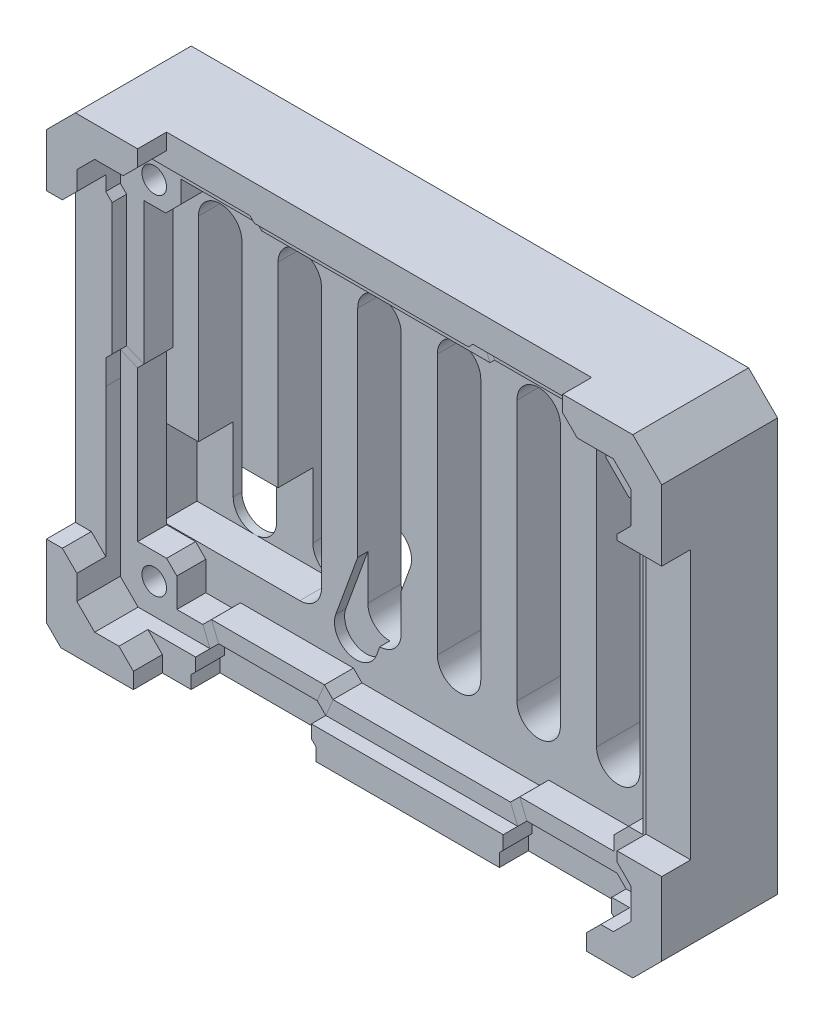
SolidWorks part; units mm, degrees
ref_plane "前视基准面" through (0, 0, 0) normal (0, 0, 1) x (1, 0, 0)
ref_plane "上视基准面" through (0, 0, 0) normal (0, 1, 0) x (1, 0, 0)
ref_plane "右视基准面" through (0, 0, 0) normal (1, 0, 0) x (0, 0, -1)
other "Configuration Table"
sketch "草图1" plane through (0, 0, 0) normal (0, 0, 1) x (1, 0, 0)
  line L1 (0, 0) -> (75, 0)
  line L2 (0, 0) -> (0, -55)
  line L3 (0, -55) -> (75, -55)
  line L4 (75, 0) -> (75, -55)
  dimension "D1" = 55
  dimension "D2" = 75
extrude "凸台-拉伸1" add sketch "草图1" along normal blind 12
sketch "草图2" plane through (0, 0, 0) normal (0, 0, -1) x (-1, 0, 0)
  circle A0 centre (-71.1669, -3.5575) radius 1.7
  circle A1 centre (-71.1669, -51.5849) radius 1.7
  circle A2 centre (-3.8888, -51.5849) radius 1.7
  circle A3 centre (-3.8888, -3.5575) radius 1.7
  dimension "D1" = 3.4
  dimension "D2" = 3.4
  dimension "D3" = 3.4
  dimension "D4" = 3.4
extrude "切除-拉伸1" cut sketch "草图2" against normal blind 12
sketch "草图3" plane through (0, 0, 0) normal (0, 0, -1) x (-1, 0, 0)
  line L1 (-73.9669, -0.7575) -> (-68.3669, -0.7575)
  line L2 (-73.9669, -0.7575) -> (-73.9669, -6.3575)
  line L3 (-73.9669, -6.3575) -> (-68.3669, -6.3575)
  line L4 (-68.3669, -0.7575) -> (-68.3669, -6.3575)
  line L5 (-73.9669, -0.7575) -> (-68.3669, -6.3575) construction
  line L6 (-73.9669, -6.3575) -> (-68.3669, -0.7575) construction
  line L11 (-6.6888, -0.7575) -> (-1.0888, -0.7575)
  line L12 (-6.6888, -0.7575) -> (-6.6888, -6.3575)
  line L13 (-6.6888, -6.3575) -> (-1.0888, -6.3575)
  line L14 (-1.0888, -0.7575) -> (-1.0888, -6.3575)
  line L15 (-6.6888, -0.7575) -> (-1.0888, -6.3575) construction
  line L16 (-6.6888, -6.3575) -> (-1.0888, -0.7575) construction
  line L17 (-73.9669, -48.7849) -> (-68.3669, -48.7849)
  line L18 (-73.9669, -48.7849) -> (-73.9669, -54.3849)
  line L19 (-73.9669, -54.3849) -> (-68.3669, -54.3849)
  line L20 (-68.3669, -48.7849) -> (-68.3669, -54.3849)
  line L21 (-73.9669, -48.7849) -> (-68.3669, -54.3849) construction
  line L22 (-73.9669, -54.3849) -> (-68.3669, -48.7849) construction
  line L23 (-6.6888, -48.7849) -> (-1.0888, -48.7849)
  line L24 (-6.6888, -48.7849) -> (-6.6888, -54.3849)
  line L25 (-6.6888, -54.3849) -> (-1.0888, -54.3849)
  line L26 (-1.0888, -48.7849) -> (-1.0888, -54.3849)
  line L27 (-6.6888, -48.7849) -> (-1.0888, -54.3849) construction
  line L28 (-6.6888, -54.3849) -> (-1.0888, -48.7849) construction
  circle A0 centre (-71.1669, -3.5575) radius 1.7 construction
  circle A1 centre (-3.8888, -3.5575) radius 1.7 construction
  circle A2 centre (-71.1669, -51.5849) radius 1.7 construction
  circle A3 centre (-3.8888, -51.5849) radius 1.7 construction
  point P0 (-71.1669, -3.5575)
  point P8 (-71.1669, -51.5849)
  point P12 (-3.8888, -3.5575)
  point P22 (-3.8888, -51.5849)
  dimension "D1" = 5.6
  dimension "D2" = 5.6
  dimension "D3" = 5.6
  dimension "D4" = 5.6
  dimension "D5" = 5.6
  dimension "D6" = 5.6
  dimension "D7" = 5.6
  dimension "D8" = 5.6
extrude "切除-拉伸2" cut sketch "草图3" along normal blind 2.5 from offset 4 offset against normal yes
sketch "草图5" plane through (0, 0, 0) normal (0, 0, -1) x (-1, 0, 0)
  line L1 (-80, 5) -> (5, 5)
  line L2 (-80, 5) -> (-80, -60)
  line L3 (-80, -60) -> (5, -60)
  line L4 (5, 5) -> (5, -60)
  line L5 (-80, 5) -> (5, -60) construction
  line L6 (-80, -60) -> (5, 5) construction
  line L10 (-75, 0) -> (0, 0) construction
  line L11 (0, 0) -> (0, -55) construction
  line L12 (-75, -55) -> (-75, 0) construction
  line L13 (-75, 0) -> (0, 0)
  line L14 (-75, 0) -> (-75, -55)
  line L15 (-75, -55) -> (0, -55)
  line L16 (0, 0) -> (0, -55)
  line L17 (0, -55) -> (-75, -55) construction
  point P0 (-37.5, -27.5)
  dimension "D1" = 65
  dimension "D2" = 85
  dimension "D3" = 5
  dimension "D4" = 5
extrude "凸台-拉伸2" add sketch "草图5" against normal up to surface (12 mm away) up to face at (2.1888, -3.5575, 12)
sketch "草图6" plane through (0, 0, 12) normal (0, 0, 1) x (1, 0, 0)
  line L56 (0.8713, -25.6658) -> (0, -26.5371)
  line L57 (0, -26.5371) -> (0, -53.0074)
  line L58 (0, -53.0074) -> (1.9926, -55)
  line L59 (1.9926, -55) -> (11.2697, -55)
  line L60 (11.2697, -55) -> (12.4616, -53.8134)
  line L61 (12.4616, -53.8134) -> (26.7436, -53.8171)
  line L62 (26.7436, -53.8171) -> (27.9265, -55)
  line L63 (27.9265, -55) -> (53.7727, -55)
  line L64 (53.7727, -55) -> (55.0435, -53.7345)
  line L65 (55.0435, -53.7345) -> (68.1524, -53.7382)
  line L66 (68.1524, -53.7382) -> (69.4142, -55)
  line L67 (69.4142, -55) -> (72.9822, -55)
  line L68 (72.9822, -55) -> (74.9747, -53.0074)
  line L69 (74.9747, -53.0074) -> (74.9747, -49.4917)
  line L70 (74.9747, -49.4917) -> (73.0283, -47.54)
  line L71 (73.0283, -47.54) -> (73.032, -7.6469)
  line L72 (73.032, -7.6469) -> (74.9747, -5.7042)
  line L73 (74.9747, -5.7042) -> (74.9747, -2.0179)
  line L74 (74.9747, -2.0179) -> (72.9822, -0.0253)
  line L75 (72.9822, -0.0253) -> (50.2451, -0.0253)
  line L76 (50.2451, -0.0253) -> (49.6148, -0.6503)
  line L77 (49.6148, -0.6503) -> (19.3949, -0.6466)
  line L78 (19.3949, -0.6466) -> (18.7736, -0.0253)
  line L79 (18.7736, -0.0253) -> (1.9926, -0.0253)
  line L80 (1.9926, -0.0253) -> (0, -2.0179)
  line L81 (0, -2.0179) -> (0, -5.9826)
  line L82 (0, -5.9826) -> (0.875, -6.8629)
  line L83 (0.875, -6.8629) -> (0.8713, -25.6658)
extrude "切除-拉伸3" cut sketch "草图6" against normal blind 2
sketch "草图7" plane through (0, 0, 10) normal (0, 0, 1) x (1, 0, 0)
  line L28 (0.875, -6.8629) -> (0.8713, -25.6658)
  line L29 (0.8713, -25.6658) -> (0, -26.5371)
  line L30 (0, -26.5371) -> (0, -53.0074)
  line L31 (0, -53.0074) -> (1.9926, -55)
  line L32 (1.9926, -55) -> (11.2697, -55)
  line L33 (11.2697, -55) -> (12.4616, -53.8134)
  line L34 (12.4616, -53.8134) -> (26.7436, -53.8171)
  line L35 (26.7436, -53.8171) -> (27.9265, -55)
  line L36 (27.9265, -55) -> (53.7727, -55)
  line L37 (53.7727, -55) -> (55.0435, -53.7345)
  line L38 (55.0435, -53.7345) -> (68.1524, -53.7382)
  line L39 (68.1524, -53.7382) -> (69.4142, -55)
  line L40 (69.4142, -55) -> (72.9822, -55)
  line L41 (72.9822, -55) -> (74.9747, -53.0074)
  line L42 (74.9747, -53.0074) -> (74.9747, -49.4917)
  line L43 (74.9747, -49.4917) -> (73.0283, -47.54)
  line L44 (73.0283, -47.54) -> (73.032, -7.6469)
  line L45 (73.032, -7.6469) -> (74.9747, -5.7042)
  line L46 (74.9747, -5.7042) -> (74.9747, -2.0179)
  line L47 (74.9747, -2.0179) -> (72.9822, -0.0253)
  line L48 (72.9822, -0.0253) -> (50.2451, -0.0253)
  line L49 (50.2451, -0.0253) -> (49.6148, -0.6503)
  line L50 (49.6148, -0.6503) -> (19.3949, -0.6466)
  line L51 (19.3949, -0.6466) -> (18.7736, -0.0253)
  line L52 (18.7736, -0.0253) -> (1.9926, -0.0253)
  line L53 (1.9926, -0.0253) -> (0, -2.0179)
  line L54 (0, -2.0179) -> (0, -5.9826)
  line L55 (0, -5.9826) -> (0.875, -6.8629)
  line L56 (0.875, -6.8629) -> (0.8713, -25.6658)
  line L57 (0.8713, -25.6658) -> (0, -26.5371)
  line L58 (0, -26.5371) -> (0, -53.0074)
  line L59 (0, -53.0074) -> (1.9926, -55)
  line L60 (1.9926, -55) -> (11.2697, -55)
  line L61 (11.2697, -55) -> (12.4616, -53.8134)
  line L62 (12.4616, -53.8134) -> (26.7436, -53.8171)
  line L63 (26.7436, -53.8171) -> (27.9265, -55)
  line L64 (27.9265, -55) -> (53.7727, -55)
  line L65 (53.7727, -55) -> (55.0435, -53.7345)
  line L66 (55.0435, -53.7345) -> (68.1524, -53.7382)
  line L67 (68.1524, -53.7382) -> (69.4142, -55)
  line L68 (69.4142, -55) -> (72.9822, -55)
  line L69 (72.9822, -55) -> (74.9747, -53.0074)
  line L70 (74.9747, -53.0074) -> (74.9747, -49.4917)
  line L71 (74.9747, -49.4917) -> (73.0283, -47.54)
  line L72 (73.0283, -47.54) -> (73.032, -7.6469)
  line L73 (73.032, -7.6469) -> (74.9747, -5.7042)
  line L74 (74.9747, -5.7042) -> (74.9747, -2.0179)
  line L75 (74.9747, -2.0179) -> (72.9822, -0.0253)
  line L76 (72.9822, -0.0253) -> (50.2451, -0.0253)
  line L77 (50.2451, -0.0253) -> (49.6148, -0.6503)
  line L78 (49.6148, -0.6503) -> (19.3949, -0.6466)
  line L79 (19.3949, -0.6466) -> (18.7736, -0.0253)
  line L80 (18.7736, -0.0253) -> (1.9926, -0.0253)
  line L81 (1.9926, -0.0253) -> (0, -2.0179)
  line L82 (0, -2.0179) -> (0, -5.9826)
  line L83 (0, -5.9826) -> (0.875, -6.8629)
  dimension "D1" = 0
sketch "草图8" plane through (47.4663, -29.6173, 16.8349) normal (0, 1, 0) x (1, 0, 0)
  line L0 (-52.4663, 4.8349) -> (32.5337, 4.8349) construction
  line L1 (-47.4663, 6.8349) -> (-48.2663, 6.8349)
  line L2 (-47.4663, 6.8349) -> (-47.4663, 4.8349)
  line L3 (-47.4663, 4.8349) -> (-48.2663, 4.8349)
  line L4 (-48.2663, 6.8349) -> (-48.2663, 4.8349)
  dimension "D1" = 0.8
  dimension "D2" = 2
sweep "切除-扫描1" cut profiles "草图8" path "草图7"
sketch "草图9" plane through (0, 0, 10) normal (0, 0, 1) x (1, 0, 0)
  line L56 (0.8713, -25.6658) -> (0, -26.5371)
  line L57 (0, -26.5371) -> (0, -53.0074)
  line L58 (0, -53.0074) -> (1.9926, -55)
  line L59 (1.9926, -55) -> (11.2697, -55)
  line L60 (11.2697, -55) -> (12.4616, -53.8134)
  line L61 (12.4616, -53.8134) -> (26.7436, -53.8171)
  line L62 (26.7436, -53.8171) -> (27.9265, -55)
  line L63 (27.9265, -55) -> (53.7727, -55)
  line L64 (53.7727, -55) -> (55.0435, -53.7345)
  line L65 (55.0435, -53.7345) -> (68.1524, -53.7382)
  line L66 (68.1524, -53.7382) -> (69.4142, -55)
  line L67 (69.4142, -55) -> (72.9822, -55)
  line L68 (72.9822, -55) -> (74.9747, -53.0074)
  line L69 (74.9747, -53.0074) -> (74.9747, -49.4917)
  line L70 (74.9747, -49.4917) -> (73.0283, -47.54)
  line L71 (73.0283, -47.54) -> (73.032, -7.6469)
  line L72 (73.032, -7.6469) -> (74.9747, -5.7042)
  line L73 (74.9747, -5.7042) -> (74.9747, -2.0179)
  line L74 (74.9747, -2.0179) -> (72.9822, -0.0253)
  line L75 (72.9822, -0.0253) -> (50.2451, -0.0253)
  line L76 (50.2451, -0.0253) -> (49.6148, -0.6503)
  line L77 (49.6148, -0.6503) -> (19.3949, -0.6466)
  line L78 (19.3949, -0.6466) -> (18.7736, -0.0253)
  line L79 (18.7736, -0.0253) -> (1.9926, -0.0253)
  line L80 (1.9926, -0.0253) -> (0, -2.0179)
  line L81 (0, -2.0179) -> (0, -5.9826)
  line L82 (0, -5.9826) -> (0.875, -6.8629)
  line L83 (0.875, -6.8629) -> (0.8713, -25.6658)
extrude "切除-拉伸4" cut sketch "草图9" against normal blind 4
sketch "草图10" plane through (0, 0, 6) normal (0, 0, 1) x (1, 0, 0)
  line L28 (0.875, -6.8629) -> (0.8713, -25.6658)
  line L29 (0.8713, -25.6658) -> (0, -26.5371)
  line L30 (0, -26.5371) -> (0, -53.0074)
  line L31 (0, -53.0074) -> (1.9926, -55)
  line L32 (1.9926, -55) -> (11.2697, -55)
  line L33 (11.2697, -55) -> (12.4616, -53.8134)
  line L34 (12.4616, -53.8134) -> (26.7436, -53.8171)
  line L35 (26.7436, -53.8171) -> (27.9265, -55)
  line L36 (27.9265, -55) -> (53.7727, -55)
  line L37 (53.7727, -55) -> (55.0435, -53.7345)
  line L38 (55.0435, -53.7345) -> (68.1524, -53.7382)
  line L39 (68.1524, -53.7382) -> (69.4142, -55)
  line L40 (69.4142, -55) -> (72.9822, -55)
  line L41 (72.9822, -55) -> (74.9747, -53.0074)
  line L42 (74.9747, -53.0074) -> (74.9747, -49.4917)
  line L43 (74.9747, -49.4917) -> (73.0283, -47.54)
  line L44 (73.0283, -47.54) -> (73.032, -7.6469)
  line L45 (73.032, -7.6469) -> (74.9747, -5.7042)
  line L46 (74.9747, -5.7042) -> (74.9747, -2.0179)
  line L47 (74.9747, -2.0179) -> (72.9822, -0.0253)
  line L48 (72.9822, -0.0253) -> (50.2451, -0.0253)
  line L49 (50.2451, -0.0253) -> (49.6148, -0.6503)
  line L50 (49.6148, -0.6503) -> (19.3949, -0.6466)
  line L51 (19.3949, -0.6466) -> (18.7736, -0.0253)
  line L52 (18.7736, -0.0253) -> (1.9926, -0.0253)
  line L53 (1.9926, -0.0253) -> (0, -2.0179)
  line L54 (0, -2.0179) -> (0, -5.9826)
  line L55 (0, -5.9826) -> (0.875, -6.8629)
  line L56 (0.875, -6.8629) -> (0.8713, -25.6658)
  line L57 (0.8713, -25.6658) -> (0, -26.5371)
  line L58 (0, -26.5371) -> (0, -53.0074)
  line L59 (0, -53.0074) -> (1.9926, -55)
  line L60 (1.9926, -55) -> (11.2697, -55)
  line L61 (11.2697, -55) -> (12.4616, -53.8134)
  line L62 (12.4616, -53.8134) -> (26.7436, -53.8171)
  line L63 (26.7436, -53.8171) -> (27.9265, -55)
  line L64 (27.9265, -55) -> (53.7727, -55)
  line L65 (53.7727, -55) -> (55.0435, -53.7345)
  line L66 (55.0435, -53.7345) -> (68.1524, -53.7382)
  line L67 (68.1524, -53.7382) -> (69.4142, -55)
  line L68 (69.4142, -55) -> (72.9822, -55)
  line L69 (72.9822, -55) -> (74.9747, -53.0074)
  line L70 (74.9747, -53.0074) -> (74.9747, -49.4917)
  line L71 (74.9747, -49.4917) -> (73.0283, -47.54)
  line L72 (73.0283, -47.54) -> (73.032, -7.6469)
  line L73 (73.032, -7.6469) -> (74.9747, -5.7042)
  line L74 (74.9747, -5.7042) -> (74.9747, -2.0179)
  line L75 (74.9747, -2.0179) -> (72.9822, -0.0253)
  line L76 (72.9822, -0.0253) -> (50.2451, -0.0253)
  line L77 (50.2451, -0.0253) -> (49.6148, -0.6503)
  line L78 (49.6148, -0.6503) -> (19.3949, -0.6466)
  line L79 (19.3949, -0.6466) -> (18.7736, -0.0253)
  line L80 (18.7736, -0.0253) -> (1.9926, -0.0253)
  line L81 (1.9926, -0.0253) -> (0, -2.0179)
  line L82 (0, -2.0179) -> (0, -5.9826)
  line L83 (0, -5.9826) -> (0.875, -6.8629)
  dimension "D1" = 0
sketch "草图12" plane through (47.4663, -29.6173, 16.8349) normal (0, 1, 0) x (1, 0, 0)
  line L1 (25.5638, 6.8349) -> (23.9638, 6.8349)
  line L2 (25.5638, 6.8349) -> (25.5638, 10.8349)
  line L3 (25.5638, 10.8349) -> (23.9638, 10.8349)
  line L4 (23.9638, 6.8349) -> (23.9638, 10.8349)
  line L5 (25.562, 10.8349) -> (25.5657, 10.8349) construction
  dimension "D1" = 1.6
  dimension "D2" = 4
sweep "扫描1" add profiles "草图12" path "草图10"
sketch "草图13" plane through (0, 0, 6) normal (0, 0, 1) x (1, 0, 0)
  line L0 (32.4396, -35.2498) -> (27.7881, -48.0296) construction
  line L1 (32.0804, -36.2365) -> (32.7987, -34.2631) construction
  line L2 (27.429, -49.0163) -> (28.1472, -47.0429) construction
  line L3 (35.2586, -36.2759) -> (30.6072, -49.0557)
  line L4 (29.6205, -34.2237) -> (24.969, -47.0036)
  arc A0 (35.2586, -36.2759) -> (29.6205, -34.2237) centre (32.4396, -35.2498) ccw
  arc A1 (24.969, -47.0036) -> (30.6072, -49.0557) centre (27.7881, -48.0296) ccw
  point P6 (30.1138, -41.6397)
  dimension "D1" = 3
extrude "切除-拉伸5" cut sketch "草图13" against normal blind 1.4
sketch "草图15" plane through (0, 0, 6) normal (0, 0, 1) x (1, 0, 0)
  line L0 (1.5998, -47.986) -> (5.5998, -47.986)
  line L1 (1.5998, -52.3448) -> (1.5998, -27.1998) construction
  line L2 (5.5998, -47.986) -> (7.014, -49.4002)
  line L3 (7.014, -49.4002) -> (7.014, -53.4002)
  line L4 (10.6091, -53.4002) -> (2.6552, -53.4002) construction
  line L5 (7.014, -53.4002) -> (2.6552, -53.4002)
  line L6 (2.6552, -53.4002) -> (1.5998, -52.3448) construction
  line L7 (2.6552, -53.4002) -> (1.5998, -52.3448)
  line L8 (-0.8, -53.3388) -> (1.5998, -52.3448) construction
  line L9 (1.5998, -52.3448) -> (1.5998, -47.986)
  line L10 (71.4284, -48.1382) -> (69.4284, -48.1382)
  line L11 (7.5962, -1.6251) -> (7.5962, -4.6251)
  line L12 (2.6552, -1.6251) -> (18.1109, -1.6251) construction
  line L13 (69.4284, -48.1382) -> (67.4284, -50.1382)
  line L14 (67.4284, -50.1382) -> (67.4284, -52.1382)
  line L15 (68.8153, -52.1386) -> (54.383, -52.1345) construction
  line L16 (71.4302, -29.6173) -> (71.4284, -48.2013) construction
  line L17 (67.4284, -52.1382) -> (68.8153, -52.1386)
  line L18 (67.821, -54.5381) -> (68.8153, -52.1386) construction
  line L19 (68.8153, -52.1386) -> (70.0769, -53.4002)
  line L20 (69.0829, -55.8) -> (70.0769, -53.4002) construction
  line L21 (72.3195, -53.4002) -> (70.0769, -53.4002) construction
  line L22 (70.0769, -53.4002) -> (72.3195, -53.4002)
  line L23 (73.3136, -55.8) -> (72.3195, -53.4002) construction
  line L24 (72.3195, -53.4002) -> (73.3749, -52.3448)
  line L25 (73.3749, -52.3448) -> (72.3195, -53.4002) construction
  line L26 (73.3749, -52.3448) -> (73.3749, -50.1531)
  line L27 (71.4284, -48.2013) -> (73.3749, -50.1531) construction
  line L28 (75.7747, -49.161) -> (73.3749, -50.1531) construction
  line L29 (73.3749, -50.1531) -> (71.4284, -48.2013)
  line L30 (71.4284, -48.2013) -> (71.4284, -48.1382)
  line L31 (72.3195, -1.6251) -> (66.3195, -1.6251)
  line L32 (72.3195, -1.6251) -> (73.3749, -2.6805) construction
  line L33 (50.9039, -1.6251) -> (72.3195, -1.6251) construction
  line L34 (66.3195, -1.6251) -> (66.3195, -5.6251)
  line L35 (66.3195, -5.6251) -> (69.4321, -8.7377)
  line L36 (69.4321, -8.7377) -> (71.4321, -8.7377)
  line L37 (71.4321, -8.7377) -> (71.4323, -6.9842)
  line L38 (71.4323, -6.9842) -> (73.3035, -5.113)
  line L39 (73.3749, -5.0415) -> (71.4323, -6.9842) construction
  line L40 (73.3035, -5.113) -> (73.3749, -5.0415)
  line L41 (73.3749, -2.6805) -> (73.3749, -5.0415) construction
  line L42 (73.3749, -5.0415) -> (73.3749, -2.6805)
  line L43 (73.3749, -2.6805) -> (72.3195, -1.6251)
  line L44 (73.832, -7.9783) -> (71.4323, -6.9842) construction
  line L45 (71.4323, -6.9842) -> (71.4302, -29.6173) construction
  line L46 (7.5962, -4.6251) -> (5.4749, -6.7464)
  line L47 (5.4749, -6.7464) -> (2.4749, -6.7464)
  line L48 (2.471, -26.3286) -> (2.475, -6.2032) construction
  line L49 (2.4749, -6.7464) -> (2.475, -6.2032)
  line L50 (0.075, -7.1928) -> (2.475, -6.2032) construction
  line L51 (2.475, -6.2032) -> (1.5998, -5.3228) construction
  line L52 (2.475, -6.2032) -> (1.5998, -5.3228)
  line L53 (1.5998, -5.3228) -> (1.5998, -2.6805) construction
  line L54 (1.5998, -5.3228) -> (1.5998, -2.6805)
  line L55 (1.5998, -2.6805) -> (2.6552, -1.6251) construction
  line L56 (-0.8, -1.6865) -> (1.5998, -2.6805) construction
  line L57 (1.5998, -2.6805) -> (2.6552, -1.6251)
  line L58 (1.6612, 0.7747) -> (2.6552, -1.6251) construction
  line L59 (2.6552, -1.6251) -> (7.5962, -1.6251)
  circle A0 centre (3.8888, -3.5575) radius 1.7
  circle A1 centre (71.1669, -3.5575) radius 1.7
  circle A2 centre (71.1669, -51.5849) radius 1.7
  circle A3 centre (3.8888, -51.5849) radius 1.7
  dimension "D1" = 135
  dimension "D2" = 4
  dimension "D3" = 4
  dimension "D4" = 2
  dimension "D5" = 2
  dimension "D6" = 2
  dimension "D7" = 2
  dimension "D8" = 135
  dimension "D9" = 6
  dimension "D10" = 135
  dimension "D11" = 2
  dimension "6" = 4
  dimension "D12" = 3
  dimension "D13" = 3
  dimension "D14" = 3
  dimension "D15" = 135
extrude "凸台-拉伸3" add sketch "草图15" along normal up to surface (4 mm away) contours L9 L0 L2 L3 L5 L7 | L59 L11 L46 L47 L49 L52 L54 L57 | L43 L31 L34 L35 L36 L37 L38 L40 L42 | L30 L10 L13 L14 L17 L19 L22 L24 L26 L29 up to face at (10.3831, 0.1748, 10)
sketch "草图16" plane through (0, 0, 6) normal (0, 0, -1) x (-1, 0, 0)
  circle A0 centre (-3.8888, -51.5849) radius 1.7 construction
  circle A1 centre (-71.1669, -51.5849) radius 1.7 construction
  circle A2 centre (-71.1669, -3.5575) radius 1.7 construction
  circle A3 centre (-3.8888, -3.5575) radius 1.7 construction
  circle A4 centre (-3.8888, -51.5849) radius 1.7
  circle A5 centre (-71.1669, -51.5849) radius 1.7
  circle A6 centre (-71.1669, -3.5575) radius 1.7
  circle A7 centre (-3.8888, -3.5575) radius 1.7
extrude "切除-拉伸6" cut sketch "草图16" against normal up to surface (4 mm away) up to face at (70.599, -31.3771, 10)
sketch "草图17" plane through (0, 0, 6) normal (0, 0, 1) x (1, 0, 0)
  line L0 (9, -8.8523) -> (9, -44.8523) construction
  line L1 (12, -8.8523) -> (12, -44.8523)
  line L2 (6, -8.8523) -> (6, -44.8523)
  line L3 (-5, -60) -> (-5, 5) construction
  line L4 (20, -8.8523) -> (20, -44.8523) construction
  line L5 (23, -8.8523) -> (23, -44.8523)
  line L6 (17, -8.8523) -> (17, -44.8523)
  line L7 (31, -8.8523) -> (31, -44.8523) construction
  line L8 (34, -8.8523) -> (34, -44.8523)
  line L9 (28, -8.8523) -> (28, -44.8523)
  line L10 (42, -8.8523) -> (42, -44.8523) construction
  line L11 (45, -8.8523) -> (45, -44.8523)
  line L12 (39, -8.8523) -> (39, -44.8523)
  line L13 (53, -8.8523) -> (53, -44.8523) construction
  line L14 (56, -8.8523) -> (56, -44.8523)
  line L15 (50, -8.8523) -> (50, -44.8523)
  line L16 (64, -8.8523) -> (64, -44.8523) construction
  line L17 (67, -8.8523) -> (67, -44.8523)
  line L18 (61, -8.8523) -> (61, -44.8523)
  arc A0 (12, -8.8523) -> (6, -8.8523) centre (9, -8.8523) ccw
  arc A1 (6, -44.8523) -> (12, -44.8523) centre (9, -44.8523) ccw
  arc A2 (23, -8.8523) -> (17, -8.8523) centre (20, -8.8523) ccw
  arc A3 (17, -44.8523) -> (23, -44.8523) centre (20, -44.8523) ccw
  arc A4 (34, -8.8523) -> (28, -8.8523) centre (31, -8.8523) ccw
  arc A5 (28, -44.8523) -> (34, -44.8523) centre (31, -44.8523) ccw
  arc A6 (45, -8.8523) -> (39, -8.8523) centre (42, -8.8523) ccw
  arc A7 (39, -44.8523) -> (45, -44.8523) centre (42, -44.8523) ccw
  arc A8 (56, -8.8523) -> (50, -8.8523) centre (53, -8.8523) ccw
  arc A9 (50, -44.8523) -> (56, -44.8523) centre (53, -44.8523) ccw
  arc A10 (67, -8.8523) -> (61, -8.8523) centre (64, -8.8523) ccw
  arc A11 (61, -44.8523) -> (67, -44.8523) centre (64, -44.8523) ccw
  point P2 (9, -26.8523)
  point P13 (20, -26.8523)
  point P20 (31, -26.8523)
  point P27 (42, -26.8523)
  point P34 (53, -26.8523)
  point P41 (64, -26.8523)
  dimension "D1" = 3
  dimension "D2" = 36
  dimension "D3" = 14
  dimension "D4" = 6
extrude "切除-拉伸7" cut sketch "草图17" against normal up to surface (6 mm away) up to face at (2.1888, -3.5575, 0)
chamfer "倒角1" distance 4 angle 45 3 edges at (80, 5, 6) (80, -60, 6) (-5, 5, 6)
chamfer "倒角2" distance 2 angle 45 1 edges at (-5, -60, 6)
sketch "草图18" plane through (0, 0, 12) normal (0, 0, 1) x (1, 0, 0)
  line L0 (12.7918, -56.4) -> (9.1918, -60)
  line L1 (76, -60) -> (-3, -60) construction
  line L2 (9.1918, -60) -> (30.0121, -60)
  line L3 (30.0121, -60) -> (26.4121, -56.4)
  line L4 (26.4121, -56.4) -> (12.7918, -56.4)
  line L5 (26.4121, -54.617) -> (27.4064, -52.2175) construction
  line L6 (12.7918, -54.617) -> (26.4121, -54.617) construction
  line L7 (12.7918, -54.617) -> (12.7918, -60) construction
  line L8 (12.7918, -60) -> (26.4121, -60) construction
  line L9 (26.4121, -54.617) -> (26.4121, -60) construction
  line L10 (26.4121, -54.617) -> (12.7918, -54.6135) construction
  line L11 (55.3738, -54.5346) -> (54.383, -52.1345) construction
  line L12 (10.9918, -58.2) -> (10.9918, -60)
  line L13 (28.2121, -58.2) -> (28.2121, -60)
  line L14 (67.821, -54.5381) -> (55.3738, -54.5346) construction
  line L15 (55.3738, -54.5346) -> (67.781, -54.5346) construction
  line L16 (55.3738, -54.5346) -> (55.3738, -60) construction
  line L17 (55.3738, -60) -> (67.781, -60) construction
  line L18 (67.781, -54.5346) -> (67.781, -60) construction
  line L19 (55.3738, -56.4) -> (53.5738, -58.2)
  line L20 (53.5738, -58.2) -> (53.5738, -60)
  line L21 (53.5738, -60) -> (69.581, -60)
  line L22 (69.581, -60) -> (69.581, -58.2)
  line L23 (69.581, -58.2) -> (67.781, -56.4)
  line L24 (67.781, -56.4) -> (55.3738, -56.4)
  line M40 (-3, -60) -> (76, -60)
  dimension "D1" = 45
  dimension "D2" = 45
  dimension "D3" = 3.6
  dimension "D4" = 13.6203
  dimension "D5" = 12.4071
  dimension "D6" = 135
  dimension "D7" = 135
extrude "切除-拉伸8" cut sketch "草图18" against normal blind 4 contours L13 L3 L4 L0 L12 L2 | L23 L24 L19 L20 L22 M40
sketch "草图20" plane through (0, 0, 12) normal (0, 0, 1) x (1, 0, 0)
  line L0 (0.0714, -25.3343) -> (2.471, -26.3286) construction
  line L1 (2.471, -26.3286) -> (2.4749, -6.7464) construction
  line L2 (2.4749, -6.7464) -> (5.4749, -6.7464) construction
  line L3 (5.4749, -6.7464) -> (7.5962, -4.6251) construction
  line L4 (7.5962, -4.6251) -> (7.5962, -1.6251) construction
  line L5 (7.5962, -1.6251) -> (18.1109, -1.6251) construction
  line L6 (18.1109, -1.6251) -> (19.1049, 0.7747) construction
  line L7 (19.1049, 0.7747) -> (1.6612, 0.7747) construction
  line L8 (1.6612, 0.7747) -> (-0.8, -1.6865) construction
  line L9 (-0.8, -1.6865) -> (-0.8, -6.3126) construction
  line L10 (-0.8, -6.3126) -> (0.075, -7.1928) construction
  line L11 (0.075, -7.1928) -> (0.0714, -25.3343) construction
  line L12 (67.821, -54.5381) -> (69.0829, -55.8) construction
  line L13 (69.0829, -55.8) -> (73.3136, -55.8) construction
  line L14 (73.3136, -55.8) -> (75.7747, -53.3388) construction
  line L15 (75.7747, -53.3388) -> (75.7747, -49.161) construction
  line L16 (75.7747, -49.161) -> (73.8283, -47.2093) construction
  line L17 (73.8283, -47.2093) -> (73.832, -7.9783) construction
  line L18 (73.832, -7.9783) -> (75.7747, -6.0355) construction
  line L19 (75.7747, -6.0355) -> (75.7747, -1.6865) construction
  line L20 (75.7747, -1.6865) -> (73.3136, 0.7747) construction
  line L21 (73.3136, 0.7747) -> (49.9157, 0.7747) construction
  line L22 (49.9157, 0.7747) -> (50.9039, -1.6251) construction
  line L23 (50.9039, -1.6251) -> (66.3195, -1.6251) construction
  line L24 (66.3195, -1.6251) -> (66.3195, -5.6251) construction
  line L25 (66.3195, -5.6251) -> (69.4321, -8.7377) construction
  line L26 (69.4321, -8.7377) -> (71.4321, -8.7377) construction
  line L27 (71.4321, -8.7377) -> (71.4302, -29.6173) construction
  line L28 (71.4302, -29.6173) -> (71.4284, -48.1382) construction
  line L29 (71.4284, -48.1382) -> (69.4284, -48.1382) construction
  line L30 (69.4284, -48.1382) -> (67.4284, -50.1382) construction
  line L31 (67.4284, -50.1382) -> (67.4284, -52.1382) construction
  line L32 (67.4284, -52.1382) -> (54.383, -52.1345) construction
  line L33 (54.383, -52.1345) -> (55.3738, -54.5346) construction
  line L34 (55.3738, -54.5346) -> (67.821, -54.5381) construction
  line L35 (-0.8, -29.6173) -> (-0.8, -53.3388) construction
  line L36 (-0.8, -53.3388) -> (1.6612, -55.8) construction
  line L37 (1.6612, -55.8) -> (11.6, -55.8) construction
  line L38 (11.6, -55.8) -> (10.6091, -53.4002) construction
  line L39 (10.6091, -53.4002) -> (7.014, -53.4002) construction
  line L40 (7.014, -53.4002) -> (7.014, -49.4002) construction
  line L41 (7.014, -49.4002) -> (5.5998, -47.986) construction
  line L42 (5.5998, -47.986) -> (1.5998, -47.986) construction
  line L43 (1.5998, -47.986) -> (1.5998, -27.1998) construction
  line L44 (1.5998, -27.1998) -> (-0.8, -26.2057) construction
  line L45 (-0.8, -26.2057) -> (-0.8, -29.6173) construction
  line L46 (0.0714, -25.3343) -> (2.471, -26.3286)
  line L47 (2.471, -26.3286) -> (2.4749, -6.7464)
  line L48 (2.4749, -6.7464) -> (5.4749, -6.7464)
  line L49 (5.4749, -6.7464) -> (7.5962, -4.6251)
  line L50 (7.5962, -4.6251) -> (7.5962, -1.6251)
  line L51 (7.5962, -1.6251) -> (18.1109, -1.6251)
  line L52 (18.1109, -1.6251) -> (19.1049, 0.7747)
  line L53 (19.1049, 0.7747) -> (1.6612, 0.7747)
  line L54 (1.6612, 0.7747) -> (-0.8, -1.6865)
  line L55 (-0.8, -1.6865) -> (-0.8, -6.3126)
  line L56 (-0.8, -6.3126) -> (0.075, -7.1928)
  line L57 (0.075, -7.1928) -> (0.0714, -25.3343)
  line L58 (67.821, -54.5381) -> (69.0829, -55.8)
  line L59 (69.0829, -55.8) -> (73.3136, -55.8)
  line L60 (73.3136, -55.8) -> (75.7747, -53.3388)
  line L61 (75.7747, -53.3388) -> (75.7747, -49.161)
  line L62 (75.7747, -49.161) -> (73.8283, -47.2093)
  line L63 (73.8283, -47.2093) -> (73.832, -7.9783)
  line L64 (73.832, -7.9783) -> (75.7747, -6.0355)
  line L65 (75.7747, -6.0355) -> (75.7747, -1.6865)
  line L66 (75.7747, -1.6865) -> (73.3136, 0.7747)
  line L67 (73.3136, 0.7747) -> (49.9157, 0.7747)
  line L68 (49.9157, 0.7747) -> (50.9039, -1.6251)
  line L69 (50.9039, -1.6251) -> (66.3195, -1.6251)
  line L70 (66.3195, -1.6251) -> (66.3195, -5.6251)
  line L71 (66.3195, -5.6251) -> (69.4321, -8.7377)
  line L72 (69.4321, -8.7377) -> (71.4321, -8.7377)
  line L73 (71.4321, -8.7377) -> (71.4302, -29.6173)
  line L74 (71.4302, -29.6173) -> (71.4284, -48.1382)
  line L75 (71.4284, -48.1382) -> (69.4284, -48.1382)
  line L76 (69.4284, -48.1382) -> (67.4284, -50.1382)
  line L77 (67.4284, -50.1382) -> (67.4284, -52.1382)
  line L78 (67.4284, -52.1382) -> (54.383, -52.1345)
  line L79 (54.383, -52.1345) -> (55.3738, -54.5346)
  line L80 (55.3738, -54.5346) -> (67.821, -54.5381)
  line L81 (-0.8, -29.6173) -> (-0.8, -53.3388)
  line L82 (-0.8, -53.3388) -> (1.6612, -55.8)
  line L83 (1.6612, -55.8) -> (11.6, -55.8)
  line L84 (11.6, -55.8) -> (10.6091, -53.4002)
  line L85 (10.6091, -53.4002) -> (7.014, -53.4002)
  line L86 (7.014, -53.4002) -> (7.014, -49.4002)
  line L87 (7.014, -49.4002) -> (5.5998, -47.986)
  line L88 (5.5998, -47.986) -> (1.5998, -47.986)
  line L89 (1.5998, -47.986) -> (1.5998, -27.1998)
  line L90 (1.5998, -27.1998) -> (-0.8, -26.2057)
  line L91 (-0.8, -26.2057) -> (-0.8, -29.6173)
  line L92 (-0.8, -6.3126) -> (-5, -6.3126)
  line L93 (7.5962, -1.6251) -> (7.5962, 5)
  line L94 (66.3195, -1.6251) -> (66.3195, 5)
  line L95 (71.4321, -8.7377) -> (80, -8.7377)
  line L96 (73.8285, -45.8698) -> (80, -45.8698)
  line L97 (69.581, -58.2) -> (69.581, -55.8)
  line L98 (7.014, -53.4002) -> (7.014, -60)
  line L99 (1.5998, -47.986) -> (-5, -47.986)
  line L112 (26.4121, -56.4) -> (28.2121, -58.2)
  line L113 (28.2121, -58.2) -> (28.2121, -60)
  line L114 (28.2121, -60) -> (53.5738, -60)
  line L115 (53.5738, -60) -> (53.5738, -58.2)
  line L116 (53.5738, -58.2) -> (55.3738, -56.4)
  line L117 (55.3738, -56.4) -> (67.781, -56.4)
  line L118 (67.781, -56.4) -> (69.581, -58.2)
  line L119 (69.581, -58.2) -> (69.581, -60)
  line L120 (69.581, -60) -> (76, -60)
  line L121 (76, -60) -> (80, -56)
  line L122 (80, -56) -> (80, 1)
  line L123 (80, 1) -> (76, 5)
  line L124 (76, 5) -> (-1, 5)
  line L125 (-1, 5) -> (-5, 1)
  line L126 (-5, 1) -> (-5, -58)
  line L127 (-5, -58) -> (-3, -60)
  line L128 (-3, -60) -> (10.9918, -60)
  line L129 (10.9918, -60) -> (10.9918, -58.2)
  line L130 (10.9918, -58.2) -> (12.7918, -56.4)
  line L131 (12.7918, -56.4) -> (26.4121, -56.4)
  line L132 (26.4121, -56.4) -> (28.2121, -58.2)
  line L133 (28.2121, -58.2) -> (28.2121, -60)
  line L134 (28.2121, -60) -> (53.5738, -60)
  line L135 (53.5738, -60) -> (53.5738, -58.2)
  line L136 (53.5738, -58.2) -> (55.3738, -56.4)
  line L137 (55.3738, -56.4) -> (67.781, -56.4)
  line L138 (67.781, -56.4) -> (69.581, -58.2)
  line L139 (69.581, -58.2) -> (69.581, -60)
  line L140 (69.581, -60) -> (76, -60)
  line L141 (76, -60) -> (80, -56)
  line L142 (80, -56) -> (80, 1)
  line L143 (80, 1) -> (76, 5)
  line L144 (76, 5) -> (-1, 5)
  line L145 (-1, 5) -> (-5, 1)
  line L146 (-5, 1) -> (-5, -58)
  line L147 (-5, -58) -> (-3, -60)
  line L148 (-3, -60) -> (10.9918, -60)
  line L149 (10.9918, -60) -> (10.9918, -58.2)
  line L150 (10.9918, -58.2) -> (12.7918, -56.4)
  line L151 (12.7918, -56.4) -> (26.4121, -56.4)
  dimension "D1" = 0
extrude "凸台-拉伸4" add sketch "草图20" along normal blind 4
chamfer "倒角4" distance 2 angle 45 6 edges at (-0.8, -47.986, 14) (7.014, -55.8, 14) (7.5962, 0.7747, 14) (-0.8, -6.3126, 14) (66.3195, 0.7747, 14) (69.581, -55.8, 14)
sketch "草图22" plane through (17, 0, 0) normal (1, 0, 0) x (0, 0, -1)
  line L0 (-6, -29.6173) -> (-6, -48.1382) construction
  line L1 (-6, -35.8523) -> (-1.2, -35.8523)
  line L2 (-6, -35.8523) -> (-6, -47.8523)
  line L3 (-6, -47.8523) -> (-1.2, -47.8523)
  line L4 (-1.2, -35.8523) -> (-1.2, -47.8523)
  line L5 (-6, -47.8523) -> (0, -47.8523) construction
  dimension "D1" = 12
  dimension "D2" = 4.8
extrude "切除-拉伸10" cut sketch "草图22" against normal blind 16 and the other way blind 3
sketch "草图23" plane through (0, 0, 12) normal (0, 0, 1) x (1, 0, 0)
  line L0 (11.6, -55.8) -> (11.6, -57.5918)
  line L1 (27.5951, -55.8) -> (27.5951, -57.583)
  line L2 (54.1031, -55.8) -> (54.1031, -57.6707)
  line L3 (69.0829, -55.8) -> (69.0829, -57.7019)
  line L24 (69.581, -58.2) -> (69.581, -57.8)
  line L25 (69.581, -57.8) -> (71.581, -55.8)
  line L26 (71.581, -55.8) -> (69.0829, -55.8)
  line L27 (69.0829, -55.8) -> (67.821, -54.5381)
  line L28 (67.821, -54.5381) -> (55.3738, -54.5346)
  line L29 (55.3738, -54.5346) -> (54.1031, -55.8)
  line L30 (54.1031, -55.8) -> (27.5951, -55.8)
  line L31 (27.5951, -55.8) -> (26.4121, -54.617)
  line L32 (26.4121, -54.617) -> (12.7918, -54.6135)
  line L33 (12.7918, -54.6135) -> (11.6, -55.8)
  line L34 (11.6, -55.8) -> (5.014, -55.8)
  line L35 (5.014, -55.8) -> (7.014, -57.8)
  line L36 (7.014, -57.8) -> (7.014, -60)
  line L37 (7.014, -60) -> (10.9918, -60)
  line L38 (10.9918, -60) -> (10.9918, -58.2)
  line L39 (10.9918, -58.2) -> (12.7918, -56.4)
  line L40 (12.7918, -56.4) -> (26.4121, -56.4)
  line L41 (26.4121, -56.4) -> (28.2121, -58.2)
  line L42 (28.2121, -58.2) -> (28.2121, -60)
  line L43 (28.2121, -60) -> (53.5738, -60)
  line L44 (53.5738, -60) -> (53.5738, -58.2)
  line L45 (53.5738, -58.2) -> (55.3738, -56.4)
  line L46 (55.3738, -56.4) -> (67.781, -56.4)
  line L47 (67.781, -56.4) -> (69.581, -58.2)
  line L48 (69.581, -58.2) -> (69.581, -57.8)
  line L49 (69.581, -57.8) -> (71.581, -55.8)
  line L50 (71.581, -55.8) -> (69.0829, -55.8)
  line L51 (69.0829, -55.8) -> (67.821, -54.5381)
  line L52 (67.821, -54.5381) -> (55.3738, -54.5346)
  line L53 (55.3738, -54.5346) -> (54.1031, -55.8)
  line L54 (54.1031, -55.8) -> (27.5951, -55.8)
  line L55 (27.5951, -55.8) -> (26.4121, -54.617)
  line L56 (26.4121, -54.617) -> (12.7918, -54.6135)
  line L57 (12.7918, -54.6135) -> (11.6, -55.8)
  line L58 (11.6, -55.8) -> (5.014, -55.8)
  line L59 (5.014, -55.8) -> (7.014, -57.8)
  line L60 (7.014, -57.8) -> (7.014, -60)
  line L61 (7.014, -60) -> (10.9918, -60)
  line L62 (10.9918, -60) -> (10.9918, -58.2)
  line L63 (10.9918, -58.2) -> (12.7918, -56.4)
  line L64 (12.7918, -56.4) -> (26.4121, -56.4)
  line L65 (26.4121, -56.4) -> (28.2121, -58.2)
  line L66 (28.2121, -58.2) -> (28.2121, -60)
  line L67 (28.2121, -60) -> (53.5738, -60)
  line L68 (53.5738, -60) -> (53.5738, -58.2)
  line L69 (53.5738, -58.2) -> (55.3738, -56.4)
  line L70 (55.3738, -56.4) -> (67.781, -56.4)
  line L71 (67.781, -56.4) -> (69.581, -58.2)
  line M29 (69.0829, -55.8) -> (67.821, -54.5381)
  line M30 (67.821, -54.5381) -> (55.3738, -54.5346)
  line M31 (55.3738, -54.5346) -> (54.1031, -55.8)
  line M33 (27.5951, -55.8) -> (26.4121, -54.617)
  line M34 (26.4121, -54.617) -> (12.7918, -54.6135)
  line M35 (12.7918, -54.6135) -> (11.6, -55.8)
  line M41 (10.9918, -58.2) -> (12.7918, -56.4)
  line M42 (12.7918, -56.4) -> (26.4121, -56.4)
  line M43 (26.4121, -56.4) -> (28.2121, -58.2)
  line M47 (53.5738, -58.2) -> (55.3738, -56.4)
  line M48 (55.3738, -56.4) -> (67.781, -56.4)
  line M49 (67.781, -56.4) -> (69.581, -58.2)
  dimension "D1" = 0
extrude "切除-拉伸11" cut sketch "草图23" against normal up to surface (4 mm away) contours L1 L0 M33 M34 M35 M41 M42 M43 | L3 L2 M29 M30 M31 M47 M48 M49 up to face at (19.602, -58.2, 8)
